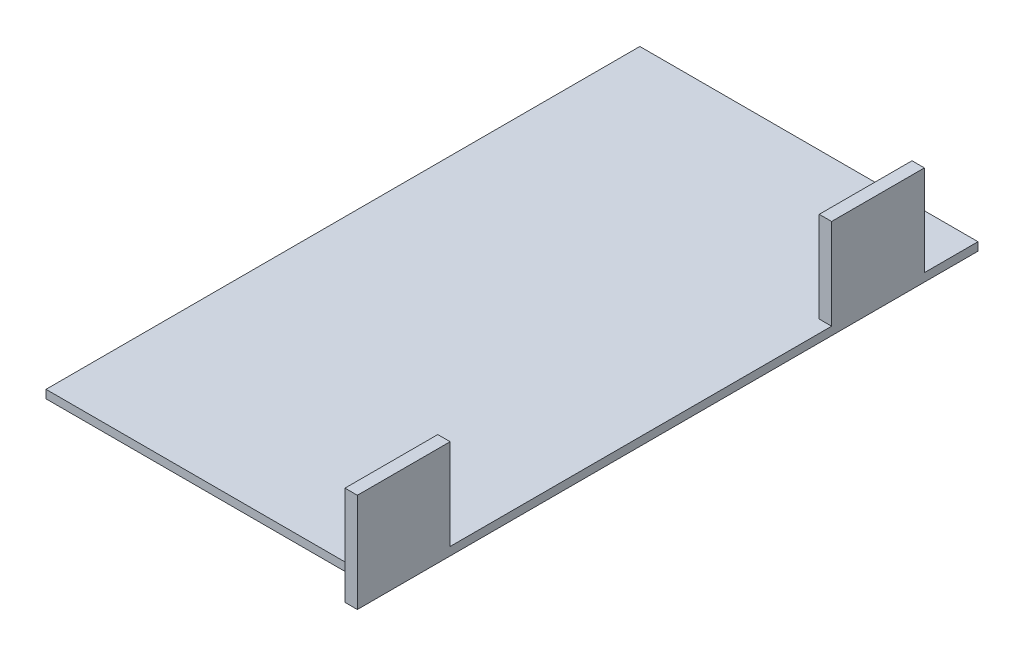
SolidWorks part; units mm, degrees
ref_plane "Alzado" through (0, 0, 0) normal (0, 0, 1) x (1, 0, 0)
ref_plane "Planta" through (0, 0, 0) normal (0, 1, 0) x (1, 0, 0)
ref_plane "Vista lateral" through (0, 0, 0) normal (1, 0, 0) x (0, 0, -1)
sketch "Croquis1" plane through (0, 0, 0) normal (0, 1, 0) x (1, 0, 0)
  line L1 (-41, 72) -> (41, 72)
  line L2 (-41, 72) -> (-41, -72)
  line L3 (-41, -72) -> (41, -72)
  line L4 (41, 72) -> (41, -72)
  line L5 (-41, 72) -> (41, -72) construction
  line L6 (-41, -72) -> (41, 72) construction
  point P0 (0, 0)
  dimension "D1" = 144
  dimension "D2" = 82
extrude "Saliente-Extruir1" add sketch "Croquis1" along normal blind 2
sketch "Croquis2" plane through (0, 0, 0) normal (0, -1, 0) x (1, 0, 0)
  line L0 (41, 72) -> (41, -72) construction
  line L1 (41, 56) -> (38, 56)
  line L2 (41, 56) -> (41, 78.5)
  line L3 (41, 78.5) -> (38, 78.5)
  line L4 (38, 56) -> (38, 78.5)
  line L5 (-41, 72) -> (41, 72) construction
  line L6 (41, -72) -> (-41, -72) construction
  line L7 (41, -59) -> (38, -59)
  line L8 (41, -59) -> (41, -36.5)
  line L9 (41, -36.5) -> (38, -36.5)
  line L10 (38, -59) -> (38, -36.5)
  dimension "D1" = 16
  dimension "D2" = 6.5
  dimension "D3" = 3
  dimension "D4" = 13
  dimension "D5" = 22.5
  dimension "D6" = 3
extrude "Saliente-Extruir4" add sketch "Croquis2" against normal blind 24
